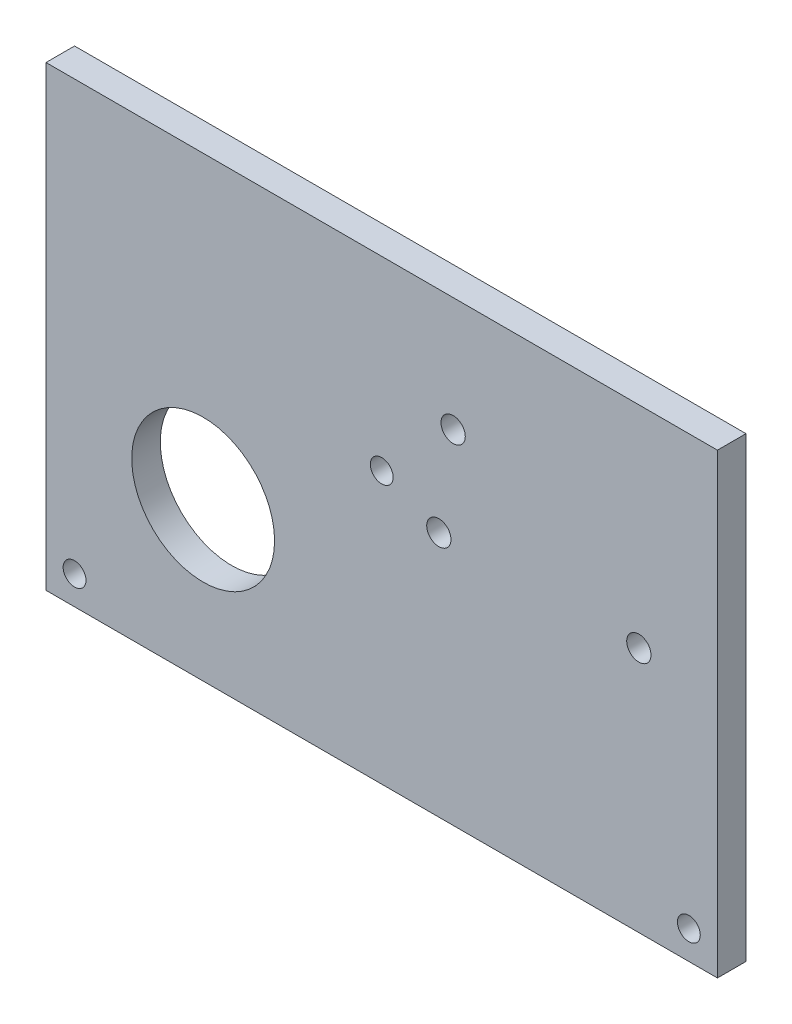
SolidWorks part; units mm, degrees
ref_plane "前视基准面" through (0, 0, 0) normal (0, 0, 1) x (1, 0, 0)
ref_plane "上视基准面" through (0, 0, 0) normal (0, 1, 0) x (1, 0, 0)
ref_plane "右视基准面" through (0, 0, 0) normal (1, 0, 0) x (0, 0, -1)
other "Configuration Table"
sketch "草图1" plane through (0, 0, 0) normal (0, 0, 1) x (1, 0, 0)
  line L1 (-92, 70) -> (2, 70)
  line L2 (-92, 70) -> (-92, 134)
  line L3 (-92, 134) -> (2, 134)
  line L4 (2, 70) -> (2, 134)
  line L5 (-92, 70) -> (2, 134) construction
  line L6 (-92, 134) -> (2, 70) construction
  circle A0 centre (-70, 92) radius 10
  circle A1 centre (-35, 118) radius 1.7
  circle A2 centre (-9, 104.5) radius 1.7
  circle A3 centre (-37, 104.5) radius 1.7
  circle A4 centre (-88, 74) radius 1.6
  circle A5 centre (-2, 74) radius 1.6
  circle A6 centre (-45, 108) radius 1.6
  point P0 (-45, 102)
extrude "凸台-拉伸1" add sketch "草图1" along normal mid plane 4
